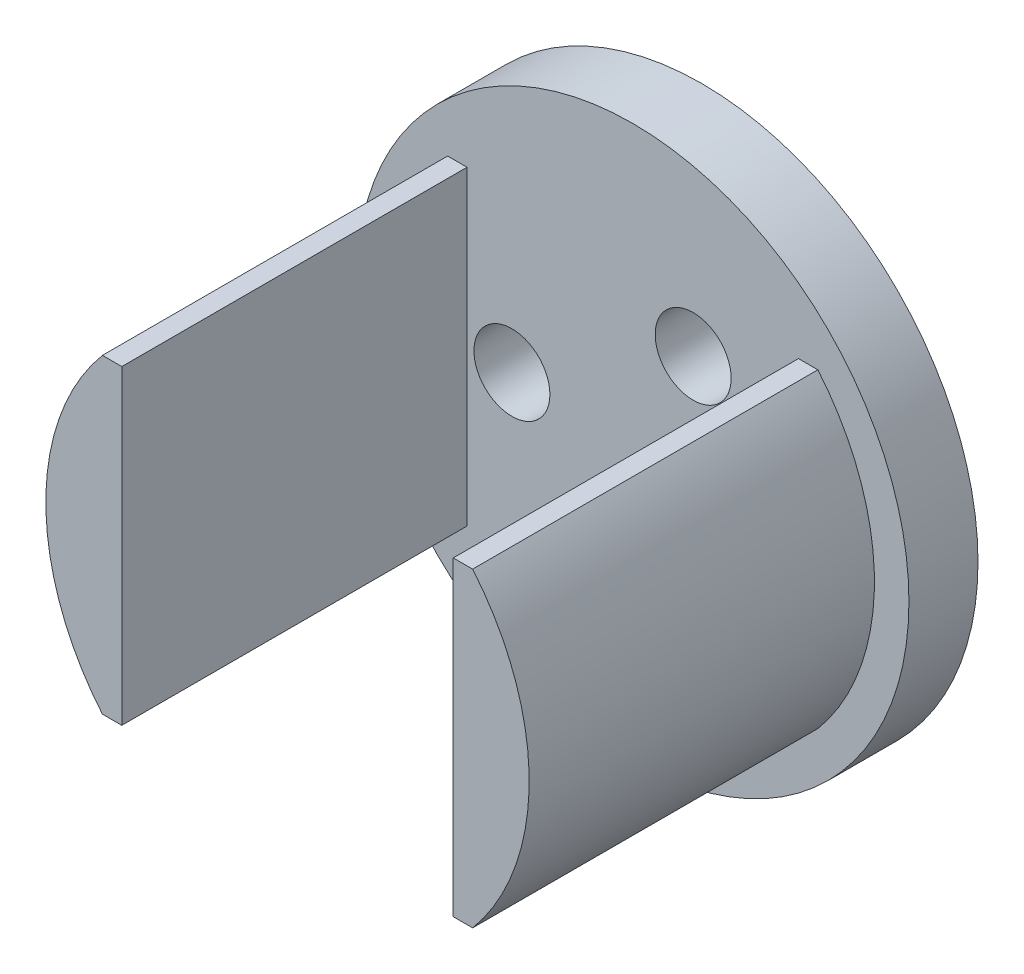
SolidWorks part; units mm, degrees
material "ABS"
ref_plane "Front Plane" through (0, 0, 0) normal (0, 0, 1) x (1, 0, 0)
ref_plane "Top Plane" through (0, 0, 0) normal (0, 1, 0) x (1, 0, 0)
ref_plane "Right Plane" through (0, 0, 0) normal (1, 0, 0) x (0, 0, -1)
sketch "Sketch1" plane through (0, 0, 0) normal (0, 0, 1) x (1, 0, 0)
  circle A0 centre (0, 0) radius 8
  circle A1 centre (0, 0) radius 3.5
  circle A2 centre (-3.5, 0) radius 1.1
  circle A3 centre (1.75, 3.0311) radius 1.1
  circle A4 centre (1.75, -3.0311) radius 1.1
  point P13 (0, 0)
  dimension "D1" = 3
extrude "Boss-Extrude1" add sketch "Sketch1" along normal blind 2 contours A0 A4 A1 A2 A3 | A4 A1 A3 A2
sketch "Sketch2" plane through (0, 0, 2) normal (0, 0, 1) x (1, 0, 0)
  line L0 (0, 0) -> (0, 4.5) construction
  line L1 (-5.3619, 4.5) -> (5.3619, 4.5)
  line L2 (4.8, -4.5) -> (4.8, 4.5)
  line L3 (-4.8, -4.5) -> (-4.8, 4.5)
  line L4 (0, 0) -> (4.8, 0) construction
  line L5 (-5.3619, -4.5) -> (5.3619, -4.5)
  circle A0 centre (0, 0) radius 7
  point P7 (0, 5)
  point P9 (4.8, 0)
  point P12 (0, 4.5)
extrude "Boss-Extrude2" add sketch "Sketch2" along normal blind 10 contours L1 A0 L5 L3 | L5 A0 L1 L2
